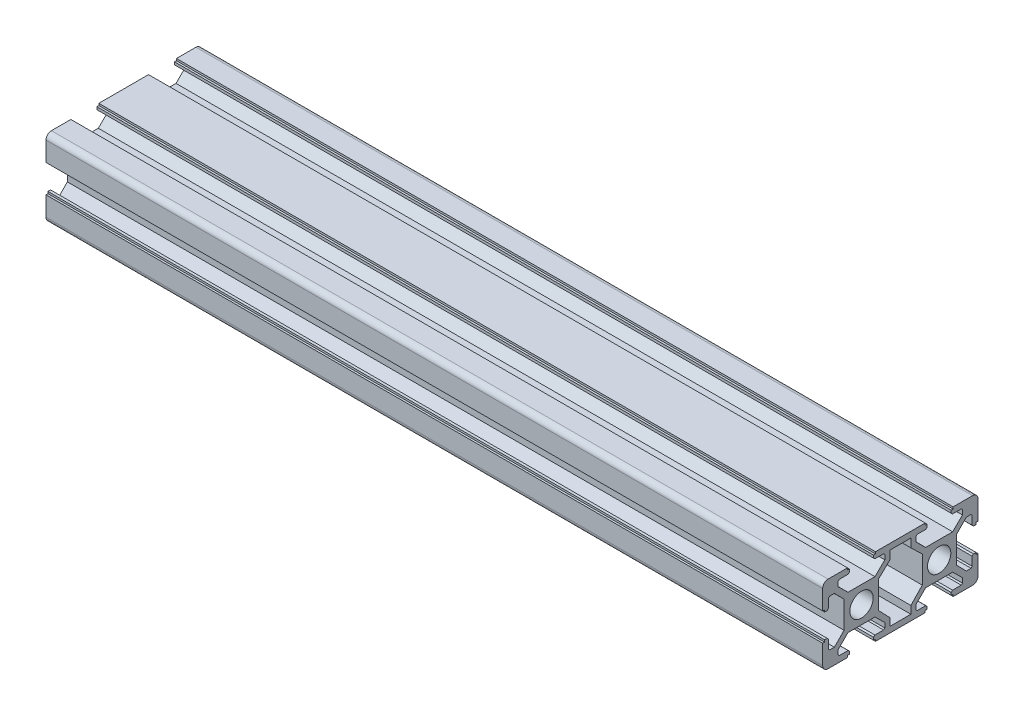
SolidWorks part; units mm, degrees
ref_plane "Спереди (Плоскость XY)" through (0, 0, 0) normal (0, 0, 1) x (1, 0, 0)
ref_plane "Сверху (Плоскость XZ)" through (0, 0, 0) normal (0, 1, 0) x (1, 0, 0)
ref_plane "Справа (Плоскость ZY)" through (0, 0, 0) normal (1, 0, 0) x (0, 0, -1)
sketch "Эскиз1" plane through (0, 0, 0) normal (1, 0, 0) x (0, 0, -1)
  line L0 (125.6534, 378.1026) -> (629.9771, 378.1026) construction
  line L1 (5.9194, 14.299) -> (45.9194, 14.299) construction
  line L2 (5.9194, 14.299) -> (5.9194, 34.299) construction
  line L3 (5.9194, 34.299) -> (45.9194, 34.299) construction
  line L4 (45.9194, 34.299) -> (45.9194, 14.299) construction
  line L5 (25.9194, 14.299) -> (25.9194, 34.299) construction
  line L6 (19.5194, 34.299) -> (24.5194, 34.299)
  line L7 (19.5194, 34.299) -> (19.5194, 33.799)
  line L8 (19.5194, 33.799) -> (19.0194, 33.799)
  line L9 (19.0194, 33.799) -> (19.0194, 33.1235)
  line L10 (19.0194, 33.1235) -> (19.3688, 32.799)
  line L11 (19.3688, 32.799) -> (21.6079, 32.799)
  line L12 (21.6079, 32.799) -> (21.9194, 32.5097)
  line L13 (21.9194, 32.5097) -> (21.9194, 31.288)
  line L14 (21.9194, 31.288) -> (19.3946, 28.799)
  line L15 (19.3946, 28.799) -> (12.4443, 28.799)
  line L16 (15.9194, 34.299) -> (15.9194, 14.299) construction
  line L17 (12.3194, 34.299) -> (7.3194, 34.299)
  line L18 (12.3194, 34.299) -> (12.3194, 33.799)
  line L19 (12.3194, 33.799) -> (12.8194, 33.799)
  line L20 (12.8194, 33.799) -> (12.8194, 33.1235)
  line L21 (12.8194, 33.1235) -> (12.4701, 32.799)
  line L22 (12.4701, 32.799) -> (10.231, 32.799)
  line L23 (10.231, 32.799) -> (9.9194, 32.5097)
  line L24 (9.9194, 32.5097) -> (9.9194, 31.288)
  line L25 (9.9194, 31.288) -> (12.4443, 28.799)
  line L26 (5.9194, 20.699) -> (5.9194, 15.699)
  line L27 (5.9194, 20.699) -> (6.4194, 20.699)
  line L28 (6.4194, 20.699) -> (6.4194, 21.199)
  line L29 (6.4194, 21.199) -> (7.095, 21.199)
  line L30 (7.095, 21.199) -> (7.4194, 20.8497)
  line L31 (7.4194, 20.8497) -> (7.4194, 18.6106)
  line L32 (7.4194, 18.6106) -> (7.7088, 18.299)
  line L33 (7.7088, 18.299) -> (8.9305, 18.299)
  line L34 (8.9305, 18.299) -> (11.4194, 20.8239)
  line L35 (11.4194, 27.7742) -> (11.4194, 20.8239)
  line L36 (8.9305, 30.299) -> (11.4194, 27.7742)
  line L37 (7.7088, 30.299) -> (8.9305, 30.299)
  line L38 (7.4194, 29.9875) -> (7.7088, 30.299)
  line L39 (7.4194, 27.7484) -> (7.4194, 29.9875)
  line L40 (7.095, 27.399) -> (7.4194, 27.7484)
  line L41 (6.4194, 27.399) -> (7.095, 27.399)
  line L42 (6.4194, 27.899) -> (6.4194, 27.399)
  line L43 (5.9194, 27.899) -> (6.4194, 27.899)
  line L44 (5.9194, 27.899) -> (5.9194, 32.899)
  line L45 (19.5194, 14.299) -> (24.5194, 14.299)
  line L46 (19.5194, 14.299) -> (19.5194, 14.799)
  line L47 (19.5194, 14.799) -> (19.0194, 14.799)
  line L48 (19.0194, 14.799) -> (19.0194, 15.4746)
  line L49 (19.0194, 15.4746) -> (19.3688, 15.799)
  line L50 (19.3688, 15.799) -> (21.6079, 15.799)
  line L51 (21.6079, 15.799) -> (21.9194, 16.0884)
  line L52 (21.9194, 16.0884) -> (21.9194, 17.31)
  line L53 (21.9194, 17.31) -> (19.3946, 19.799)
  line L54 (12.4443, 19.799) -> (19.3946, 19.799)
  line L55 (9.9194, 17.31) -> (12.4443, 19.799)
  line L56 (9.9194, 16.0884) -> (9.9194, 17.31)
  line L57 (10.231, 15.799) -> (9.9194, 16.0884)
  line L58 (12.4701, 15.799) -> (10.231, 15.799)
  line L59 (12.8194, 15.4746) -> (12.4701, 15.799)
  line L60 (12.8194, 14.799) -> (12.8194, 15.4746)
  line L61 (12.3194, 14.799) -> (12.8194, 14.799)
  line L62 (12.3194, 14.299) -> (12.3194, 14.799)
  line L63 (12.3194, 14.299) -> (7.3194, 14.299)
  line L64 (15.9194, 24.299) -> (19.3946, 28.799) construction
  line L65 (15.9194, 24.299) -> (11.4194, 27.7742) construction
  line L66 (24.5194, 34.299) -> (27.3194, 34.299)
  line L67 (24.5194, 14.299) -> (27.3194, 14.299)
  line L68 (5.9194, 24.299) -> (25.9194, 24.299) construction
  line L69 (32.3194, 14.299) -> (27.3194, 14.299)
  line L70 (32.3194, 14.299) -> (32.3194, 14.799)
  line L71 (32.3194, 14.799) -> (32.8194, 14.799)
  line L72 (32.8194, 14.799) -> (32.8194, 15.4746)
  line L73 (32.8194, 15.4746) -> (32.4701, 15.799)
  line L74 (30.231, 15.799) -> (29.9194, 16.0884)
  line L75 (32.4701, 15.799) -> (30.231, 15.799)
  line L76 (29.9194, 16.0884) -> (29.9194, 17.31)
  line L77 (29.9194, 17.31) -> (32.4443, 19.799)
  line L78 (39.3946, 19.799) -> (32.4443, 19.799)
  line L79 (41.9194, 17.31) -> (39.3946, 19.799)
  line L80 (41.9194, 16.0884) -> (41.9194, 17.31)
  line L81 (41.6079, 15.799) -> (41.9194, 16.0884)
  line L82 (39.3688, 15.799) -> (41.6079, 15.799)
  line L83 (39.0194, 15.4746) -> (39.3688, 15.799)
  line L84 (39.0194, 14.799) -> (39.0194, 15.4746)
  line L85 (39.5194, 14.799) -> (39.0194, 14.799)
  line L86 (39.5194, 14.299) -> (39.5194, 14.799)
  line L87 (39.5194, 14.299) -> (44.5194, 14.299)
  line L88 (45.9194, 20.699) -> (45.9194, 15.699)
  line L89 (45.9194, 20.699) -> (45.4194, 20.699)
  line L90 (45.4194, 20.699) -> (45.4194, 21.199)
  line L91 (45.4194, 21.199) -> (44.7439, 21.199)
  line L92 (44.7439, 21.199) -> (44.4194, 20.8497)
  line L93 (44.4194, 20.8497) -> (44.4194, 18.6106)
  line L94 (44.4194, 18.6106) -> (44.1301, 18.299)
  line L95 (44.1301, 18.299) -> (42.9084, 18.299)
  line L96 (42.9084, 18.299) -> (40.4194, 20.8239)
  line L97 (40.4194, 27.7742) -> (40.4194, 20.8239)
  line L98 (42.9084, 30.299) -> (40.4194, 27.7742)
  line L99 (44.1301, 30.299) -> (42.9084, 30.299)
  line L100 (44.4194, 29.9875) -> (44.1301, 30.299)
  line L101 (44.4194, 27.7484) -> (44.4194, 29.9875)
  line L102 (44.7439, 27.399) -> (44.4194, 27.7484)
  line L103 (45.4194, 27.399) -> (44.7439, 27.399)
  line L104 (45.4194, 27.899) -> (45.4194, 27.399)
  line L105 (45.9194, 27.899) -> (45.4194, 27.899)
  line L106 (45.9194, 27.899) -> (45.9194, 32.899)
  line L107 (39.5194, 34.299) -> (44.5194, 34.299)
  line L108 (39.5194, 34.299) -> (39.5194, 33.799)
  line L109 (39.5194, 33.799) -> (39.0194, 33.799)
  line L110 (39.0194, 33.799) -> (39.0194, 33.1235)
  line L111 (39.0194, 33.1235) -> (39.3688, 32.799)
  line L112 (39.3688, 32.799) -> (41.6079, 32.799)
  line L113 (41.6079, 32.799) -> (41.9194, 32.5097)
  line L114 (41.9194, 32.5097) -> (41.9194, 31.288)
  line L115 (41.9194, 31.288) -> (39.3946, 28.799)
  line L116 (32.4443, 28.799) -> (39.3946, 28.799)
  line L117 (29.9194, 31.288) -> (32.4443, 28.799)
  line L118 (29.9194, 32.5097) -> (29.9194, 31.288)
  line L119 (30.231, 32.799) -> (29.9194, 32.5097)
  line L120 (32.4701, 32.799) -> (30.231, 32.799)
  line L121 (32.8194, 33.1235) -> (32.4701, 32.799)
  line L122 (32.8194, 33.799) -> (32.8194, 33.1235)
  line L123 (32.3194, 33.799) -> (32.8194, 33.799)
  line L124 (32.3194, 34.299) -> (32.3194, 33.799)
  line L125 (32.3194, 34.299) -> (27.3194, 34.299)
  line L126 (28.6271, 32.799) -> (23.2118, 32.799)
  line L127 (23.2118, 32.799) -> (23.2118, 30.6025)
  line L128 (23.2118, 30.6025) -> (20.2723, 27.7742)
  line L129 (20.2723, 27.7742) -> (20.2723, 20.8239)
  line L130 (20.2723, 20.8239) -> (23.2118, 17.769)
  line L131 (23.2118, 17.769) -> (23.2118, 15.799)
  line L132 (23.2118, 15.799) -> (28.6271, 15.799)
  line L133 (28.6271, 17.769) -> (28.6271, 15.799)
  line L134 (31.5666, 20.8239) -> (28.6271, 17.769)
  line L135 (31.5666, 27.7742) -> (31.5666, 20.8239)
  line L136 (28.6271, 30.6025) -> (31.5666, 27.7742)
  line L137 (28.6271, 32.799) -> (28.6271, 30.6025)
  arc A0 (7.3194, 14.299) -> (5.9194, 15.699) centre (7.3194, 15.699) cw
  arc A1 (5.9194, 32.899) -> (7.3194, 34.299) centre (7.3194, 32.899) cw
  arc A2 (44.5194, 14.299) -> (45.9194, 15.699) centre (44.5194, 15.699) ccw
  arc A3 (45.9194, 32.899) -> (44.5194, 34.299) centre (44.5194, 32.899) ccw
  circle A4 centre (15.9194, 24.299) radius 3
  circle A5 centre (35.9194, 24.299) radius 3
  point P20 (19.0194, 33.4612)
  point P31 (15.9194, 28.799)
  point P33 (15.9194, 24.299)
  point P151 (25.9194, 15.799)
  point P156 (25.9194, 32.799)
  dimension "D8" = 40
  dimension "D1" = 10
  dimension "D2" = 3.1
  dimension "D3" = 6
  dimension "D4" = 0.5
  dimension "D5" = 20
  dimension "D6" = 4
  dimension "D7" = 5
  dimension "D10" = 90
  dimension "D9" = 3
extrude "Бобышка-Вытянуть1" add sketch "Эскиз1" along normal blind 200 contours L106 A3 L107 L108 L109 L110 L111 L112 L113 L114 L115 L116 L117 L118 L119 L120 L121 L122 L123 L124 L125 L66 L6 L7 L8 L9 L10 L11 L12 L13 L14 L15 L25 L24 L23 L22 L21 L20 L19 L18 L17 A1 L44 L43 L42 L41 L40 L39 L38 L37 L36 | A4
